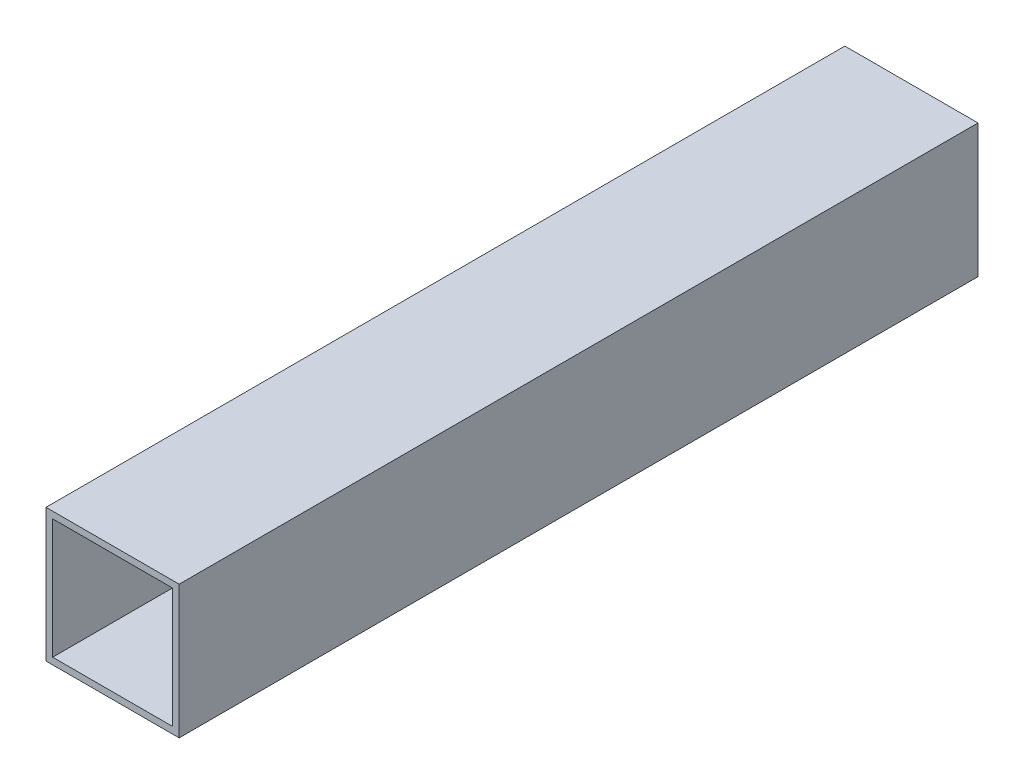
SolidWorks part; units mm, degrees
ref_plane "前视基准面" through (0, 0, 0) normal (0, 0, 1) x (1, 0, 0)
ref_plane "上视基准面" through (0, 0, 0) normal (0, 1, 0) x (1, 0, 0)
ref_plane "右视基准面" through (0, 0, 0) normal (1, 0, 0) x (0, 0, -1)
sketch "草图1" plane through (0, 0, 0) normal (0, 0, 1) x (1, 0, 0)
  line L1 (0, 0) -> (10, 0)
  line L2 (0, 0) -> (0, 10)
  line L3 (0, 10) -> (10, 10)
  line L4 (10, 0) -> (10, 10)
  line L5 (0.5, 9.5) -> (9.5, 9.5)
  line L6 (0.5, 9.5) -> (0.5, 0.5)
  line L7 (0.5, 0.5) -> (9.5, 0.5)
  line L8 (9.5, 9.5) -> (9.5, 0.5)
  dimension "D1" = 10
  dimension "D2" = 10
  dimension "D3" = 0.5
  dimension "D4" = 0.5
  dimension "D5" = 0.5
  dimension "D6" = 0.5
extrude "凸台-拉伸1" add sketch "草图1" along normal blind 60
